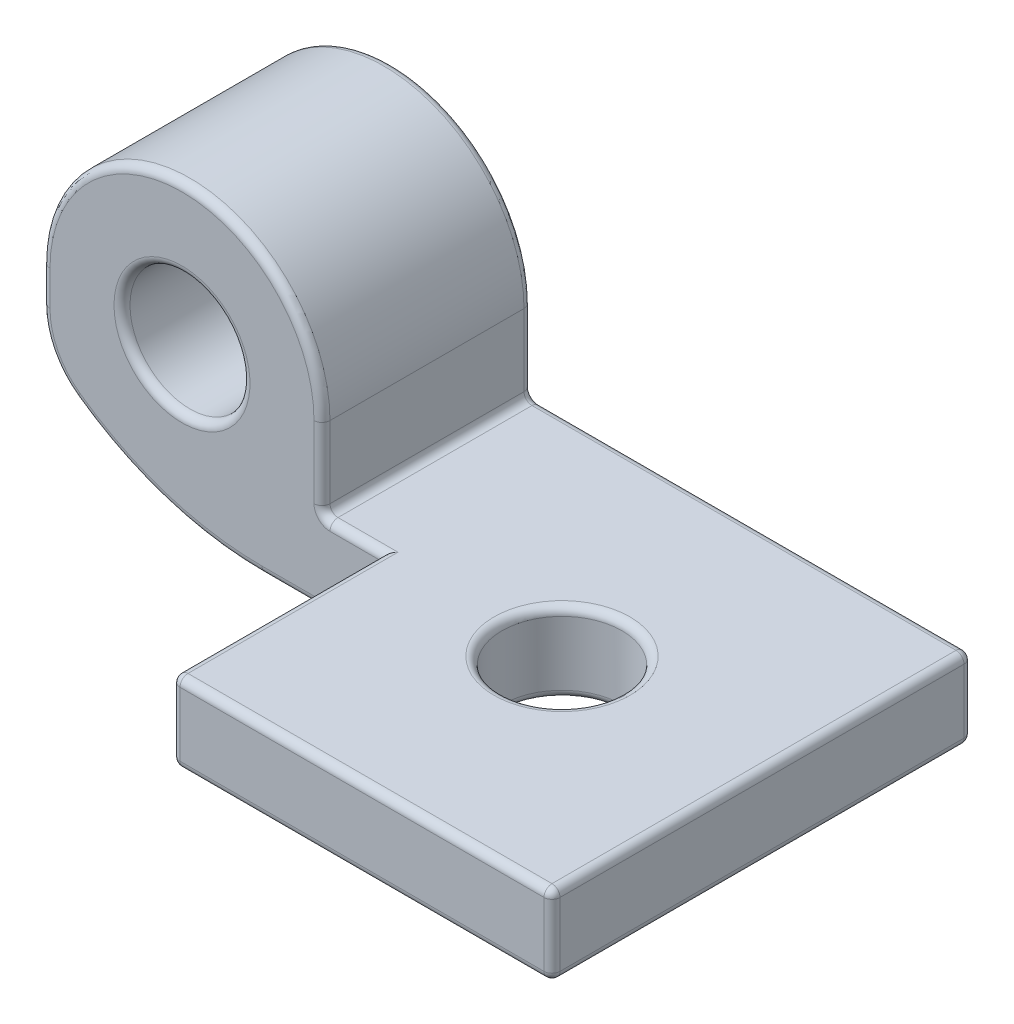
SolidWorks part; units mm, degrees
ref_plane "Plan de face" through (0, 0, 0) normal (0, 0, 1) x (1, 0, 0)
ref_plane "Plan de dessus" through (0, 0, 0) normal (0, 1, 0) x (1, 0, 0)
ref_plane "Plan de droite" through (0, 0, 0) normal (1, 0, 0) x (0, 0, -1)
sketch "Esquisse1" plane through (0, 0, 0) normal (0, 0, 1) x (1, 0, 0)
  line L0 (-3.5, -1.8095) -> (-3.5, 0)
  line L1 (3.5, 0) -> (3.5, -2)
  line L2 (3.5, -2) -> (14.5, -2)
  line L3 (14.5, -2) -> (14.5, -4)
  line L4 (14.5, -4) -> (2, -4)
  circle A0 centre (0, 0) radius 1.5
  arc A1 (-3.5, 0) -> (3.5, 0) centre (0, 0) cw
  arc A2 (-3.5, -1.8095) -> (2, -4) centre (2, 4) ccw
  point P12 (-3.5, -2.2769)
  point P14 (0, 0)
  dimension "D1" = 3
  dimension "D2" = 3.5
  dimension "D6" = 8
  dimension "D3" = 2
  dimension "D4" = 14.5
  dimension "D5" = 4
  dimension "D7" = 2
extrude "Boss.-Extru.1" add sketch "Esquisse1" along normal mid plane 10.5
sketch "Esquisse2" plane through (0, 0, 0) normal (0, 1, 0) x (1, 0, 0)
  line L0 (-3.5, -5.25) -> (-3.5, 5.25) construction
  line L1 (-3.5, 0) -> (5, 0)
  line L2 (-3.5, 0) -> (-3.5, -5.25)
  line L3 (-3.5, -5.25) -> (5, -5.25)
  line L4 (5, 0) -> (5, -5.25)
  line L5 (14.5, -5.25) -> (3.5, -5.25) construction
  dimension "D1" = 5
extrude "Enlèv. mat.-Extru.1" cut sketch "Esquisse2" against normal through all both and the other way through all
sketch "Esquisse3" plane through (0, -2, 0) normal (0, 1, 0) x (1, 0, 0)
  line L0 (14.5, -5.25) -> (14.5, 5.25) construction
  circle A0 centre (9.5, 0) radius 1.5
  point P2 (0, 0)
  dimension "D1" = 3
  dimension "D2" = 5
extrude "Enlèv. mat.-Extru.2" cut sketch "Esquisse3" against normal up to next
fillet "Congé1" radius 2 1 edges at (-3.5, -1.8095, -2.625)
fillet "Congé2" radius 0.2 26 edges at (-3.2795, -1.7863, 0) (5, -4, 2.625) (3.5, -4, 0) (5, -3, 5.25) (-3.5, -0.4367, 0) (-1.5, 0, 0) (3.5, -1, 0) (4.25, -2, 0) (-0.4512, -3.6152, 0) (1.5, 0, -5.25) (0, 3.5, -5.25) (-3.5, -0.4367, -5.25) (-0.4512, -3.6152, -5.25) (8.25, -4, -5.25) (14.5, -3, -5.25) (9, -2, -5.25) (3.5, -1, -5.25) (9.75, -4, 5.25) (14.5, -3, 5.25) (9.75, -2, 5.25) (3.5, -2, -2.625) (14.5, -2, 0) (14.5, -4, 0) (5, -2, 2.625) (-3.2795, -1.7863, -5.25) (0, 3.5, 0)
fillet "Congé3" radius 0.2 2 edges at (8, -4, 0) (9.5, -2, 1.5)
